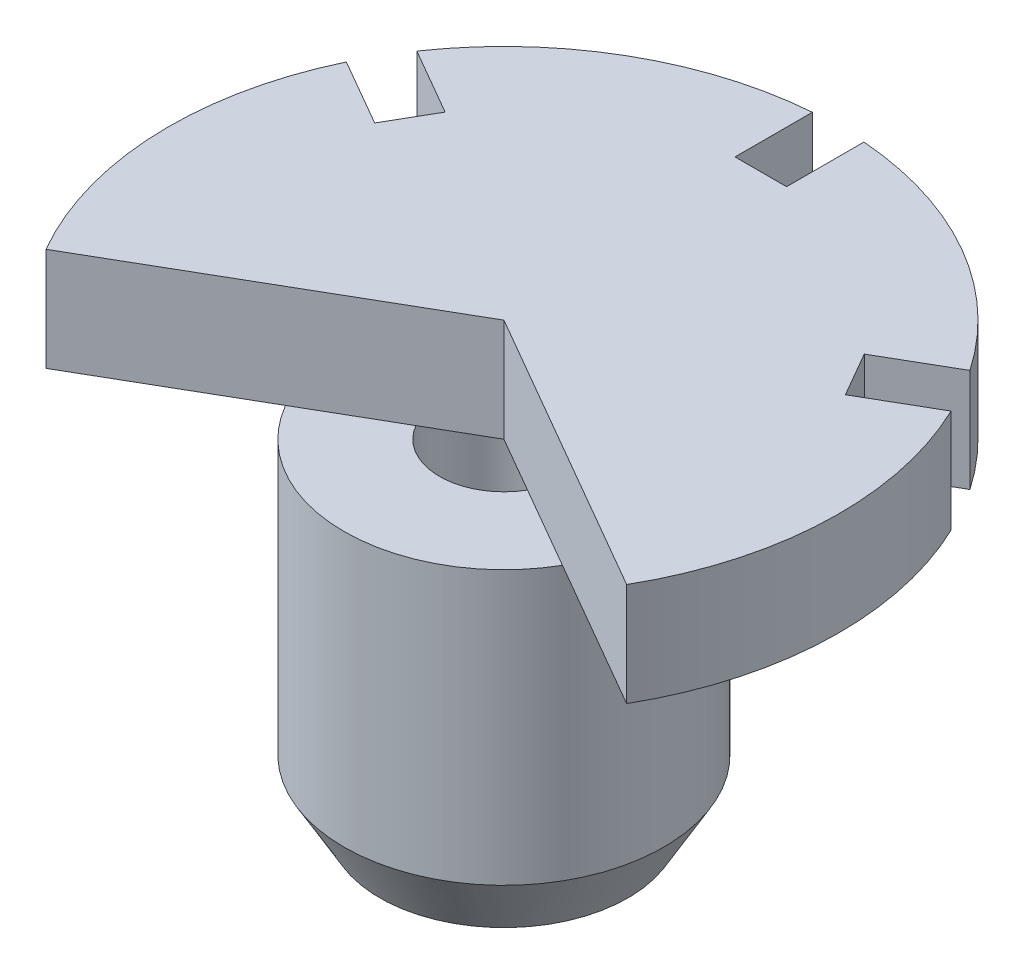
SolidWorks part; units mm, degrees
ref_plane "Piano frontale" through (0, 0, 0) normal (0, 0, 1) x (1, 0, 0)
ref_plane "Piano superiore" through (0, 0, 0) normal (0, 1, 0) x (1, 0, 0)
ref_plane "Piano destro" through (0, 0, 0) normal (1, 0, 0) x (0, 0, -1)
sketch "Schizzo1" plane through (0, 0, 0) normal (0, 1, 0) x (1, 0, 0)
  line L0 (0, 88.203) -> (0, -88.327) construction
  line L1 (0, 0) -> (-56.2917, -32.5)
  line L2 (0, 0) -> (56.2917, -32.5)
  line L3 (-5, 64.8074) -> (-5, 49.8074)
  line L4 (-5, 49.8074) -> (5, 49.8074)
  line L5 (5, 64.8074) -> (5, 49.8074)
  line L9 (53.6249, 36.7338) -> (40.6345, 29.2338)
  line L10 (-58.6249, 28.0736) -> (-45.6345, 20.5736)
  line L11 (-53.6249, 36.7338) -> (-40.6345, 29.2338)
  line L12 (-45.6345, 20.5736) -> (-40.6345, 29.2338)
  line L13 (-76.386, 44.1015) -> (76.4934, -44.1635) construction
  line L14 (58.6249, 28.0736) -> (45.6345, 20.5736)
  line L15 (40.6345, 29.2338) -> (45.6345, 20.5736)
  line L16 (76.386, 44.1015) -> (-76.4934, -44.1635) construction
  arc A0 (-5, 64.8074) -> (-53.6249, 36.7338) centre (0, 0) ccw
  arc A1 (56.2917, -32.5) -> (58.6249, 28.0736) centre (0, 0) ccw
  arc A2 (-58.6249, 28.0736) -> (-56.2917, -32.5) centre (0, 0) ccw
  arc A3 (53.6249, 36.7338) -> (5, 64.8074) centre (0, 0) ccw
  point P11 (0, 49.8074)
  point P19 (0, 0)
  point P29 (0, 0)
  point P30 (0, 0)
  dimension "D2" = 130
  dimension "D1" = 60
  dimension "D3" = 10
  dimension "D4" = 15
  dimension "D6" = 60
  dimension "D7" = 2
  dimension "D8" = 60
  dimension "D5" = 2
extrude "Estrusione-Estrusione1" add sketch "Schizzo1" along normal blind 20
sketch "Schizzo2" plane through (0, 0, 0) normal (0, -1, 0) x (1, 0, 0)
  circle A0 centre (0, 0) radius 31
  dimension "D1" = 62
extrude "Estrusione-Estrusione2" add sketch "Schizzo2" along normal blind 65
sketch "Schizzo3" plane through (0, -65, 0) normal (0, -1, 0) x (1, 0, 0)
  circle A0 centre (0, 0) radius 20
  dimension "D1" = 40
extrude "Taglio-Estrusione1" cut sketch "Schizzo3" against normal blind 26
hole_wizard "Foro Ø25.0 (25)-1" positions "Schizzo4" profile "Schizzo5" hole size "Ø25.0" standard "ISO" end condition up to next
sketch "Schizzo4" plane through (0, -39, 0) normal (0, -1, 0) x (-1, 0, 0)
  point P0 (0, 0)
sketch "Schizzo5" plane through (0, -39, 0) normal (1, 0, 0) x (0, 0, -1)
  line L0 (0, 0) -> (0, 39)
  line L1 (0, 39) -> (12.5, 39)
  line L2 (12.5, 39) -> (12.5, 0)
  line L5 (12.5, 0) -> (0, 0)
  line L11 (0, -6.35) -> (0, 107.95) construction
  dimension "Thru Hole Dia." = 25
  dimension "Thru Hole Depth" = 39
ref_plane "Piano1" through (0, 0, -31) normal (0, 0, -1) x (-1, 0, 0)
hole_wizard "Foro Ø6.0 (6)-1" positions "Schizzo6" profile "Schizzo7" hole size "Ø6.0" standard "ISO"
sketch "Schizzo6" plane through (0, 0, -31) normal (0, 0, -1) x (-1, 0, 0)
  line L0 (0, 0) -> (0, -65) construction
  line L1 (-31, -65) -> (31, -65) construction
  point P7 (0, -13)
  dimension "D1" = 52
sketch "Schizzo7" plane through (0, -13, -31) normal (1, 0, 0) x (0, 1, 0)
  line L0 (0, 0) -> (0, 18.5)
  line L1 (0, 18.5) -> (3, 18.5)
  line L2 (3, 18.5) -> (3, 0)
  line L5 (3, 0) -> (0, 0)
  line L11 (0, -6.35) -> (0, 107.95) construction
  dimension "Thru Hole Dia." = 6
  dimension "Thru Hole Depth" = 18.5
chamfer "Smusso1" distance 12 angle 30 1 edges at (0, -65, -31)
sketch "Schizzo9" plane through (0, -65, 0) normal (0, -1, 0) x (1, 0, 0)
  line L0 (0, 0) -> (0, -72.5402)
